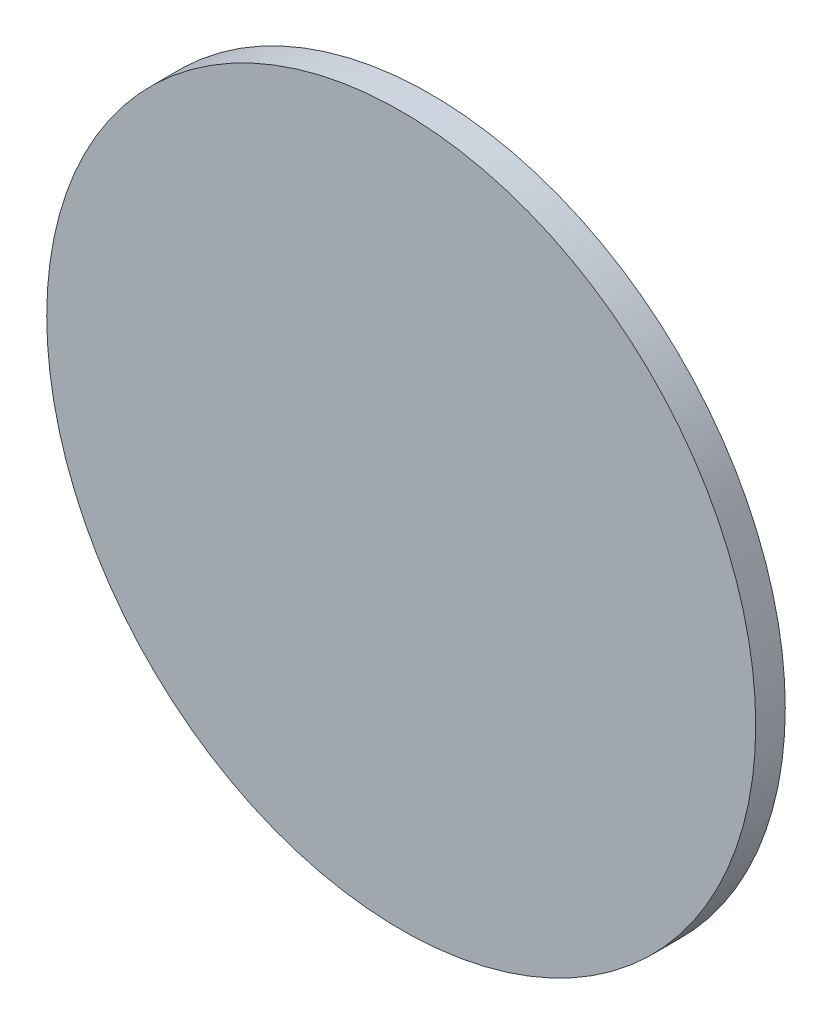
SolidWorks part; units mm, degrees
material "Oak"
ref_plane "Front Plane" through (0, 0, 0) normal (0, 0, 1) x (1, 0, 0)
ref_plane "Top Plane" through (0, 0, 0) normal (0, 1, 0) x (1, 0, 0)
ref_plane "Right Plane" through (0, 0, 0) normal (1, 0, 0) x (0, 0, -1)
sketch "Sketch1" plane through (0, 0, 0) normal (0, 0, 1) x (1, 0, 0)
  circle A0 centre (0, 0) radius 152.4
  dimension "D1" = 304.8
extrude "Boss-Extrude1" add sketch "Sketch1" along normal blind 12.7
